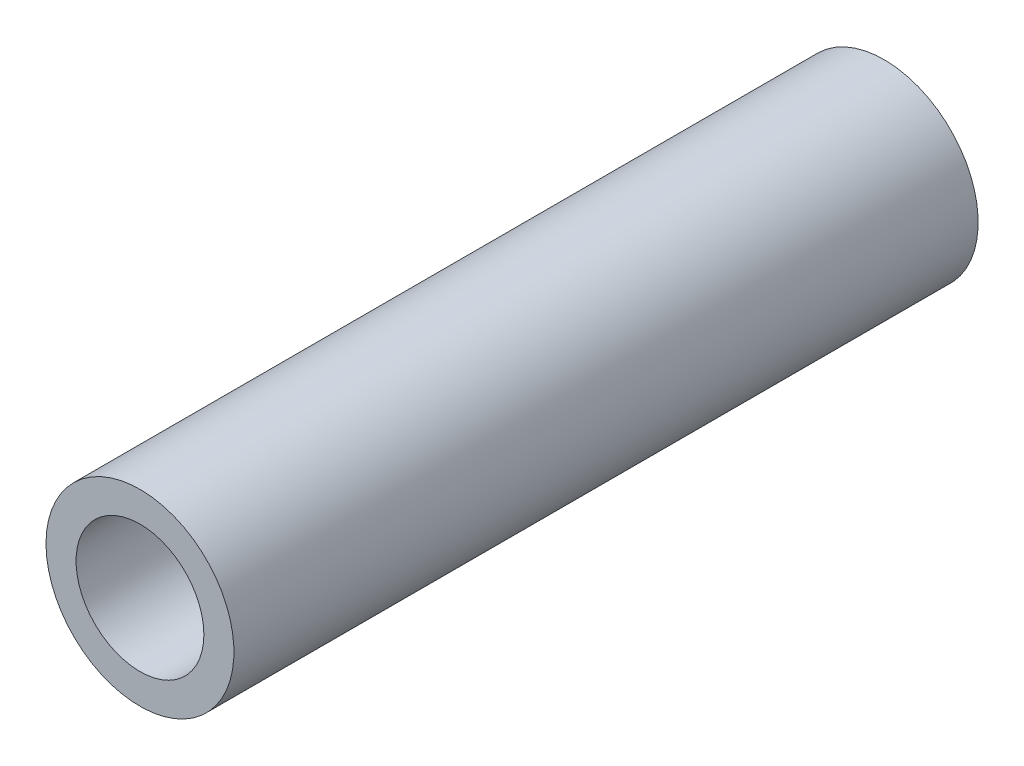
SolidWorks part; units mm, degrees
ref_plane "Front Plane" through (0, 0, 0) normal (1, 0, 0) x (0, 1, 0)
ref_plane "Top Plane" through (0, 0, 0) normal (0, 0, 1) x (0, 1, 0)
ref_plane "Right Plane" through (0, 0, 0) normal (0, 1, 0) x (-1, 0, 0)
sketch "Sketch1" plane through (0, 0, 0) normal (0, 0, 1) x (0, 1, 0)
  circle A0 centre (0, 0) radius 2.5
  dimension "D1" = 5
extrude "Boss-Extrude1" add sketch "Sketch1" along normal blind 19.8
sketch "Sketch2" plane through (0, 0, 19.8) normal (0, 0, 1) x (1, 0, 0)
  circle A0 centre (0, 0) radius 1.7
  dimension "D1" = 3.4
extrude "Cut-Extrude1" cut sketch "Sketch2" against normal through all both and the other way through all
